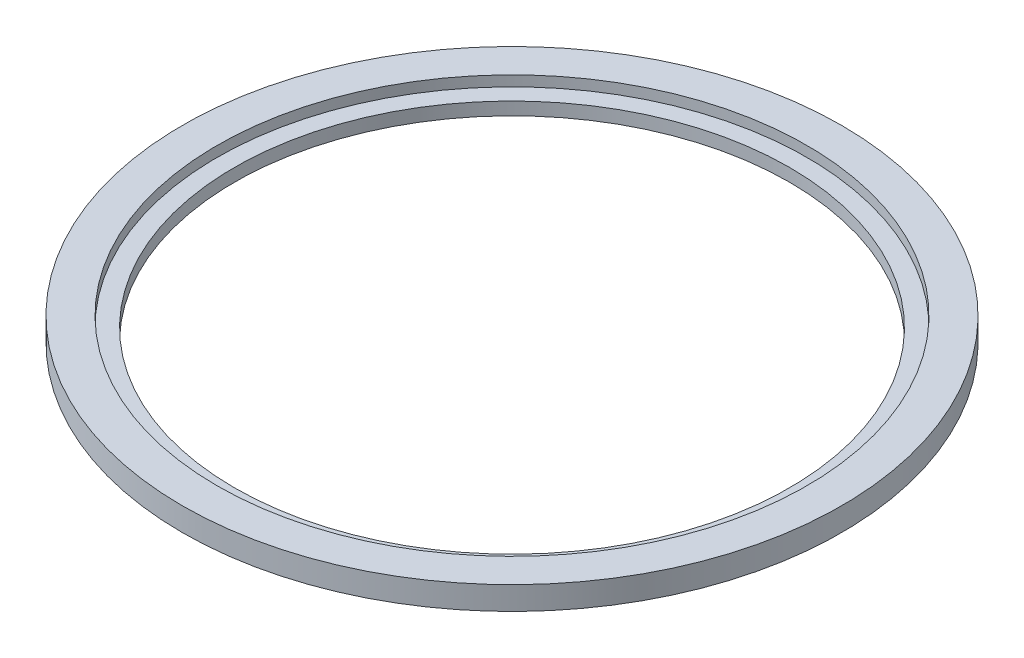
SolidWorks part; units mm, degrees
material "Balsa"
ref_plane "Front Plane" through (0, 0, 0) normal (0, 0, 1) x (1, 0, 0)
ref_plane "Top Plane" through (0, 0, 0) normal (0, 1, 0) x (1, 0, 0)
ref_plane "Right Plane" through (0, 0, 0) normal (1, 0, 0) x (0, 0, -1)
sketch "Sketch1" plane through (0, 0, 0) normal (0, 1, 0) x (1, 0, 0)
  circle A0 centre (0, 0) radius 95
  circle A1 centre (0, 0) radius 80
  dimension "D1" = 95
  dimension "D2" = 80
extrude "Boss-Extrude1" add sketch "Sketch1" along normal blind 6.7 contours A0
sketch "Sketch2" plane through (0, 6.7, 0) normal (0, 1, 0) x (1, 0, 0)
  circle A0 centre (0, 0) radius 85
  dimension "D1" = 85
extrude "Cut-Extrude1" cut sketch "Sketch2" against normal blind 3
equation "\"Ring inner radius\"= 80mm"
equation "\"D1@Sketch1\" = \"Bottom ring outer radius\""
equation "\"Heart cable hole radius\"= 3.5mm"
equation "\"Dogbone radius\"= 3mm"
equation "\"Tree side stock thickness\"= 6.7mm"
equation "\"Ring stock thickness\"= 6.7mm"
equation "\"D1@Boss-Extrude1\"= \"Ring stock thickness\""
equation "\"Tree teeth\"= 15mm"
equation "\"Tree slot\"= 15mm"
equation "\"Bottom ring outer radius\"= \"Ring inner radius\" + \"Tree teeth\""
equation "\"Cut-Extrude Tolerance\"= 5mm"
equation "\"Ring outer radius\"= \"Ring inner radius\" + \"Tree slot\" + 10"
equation "\"D2@Sketch1\"= \"Ring inner radius\""
equation "\"Plexiglass step\"= 5mm"
equation "\"Plexiglass thickness\"= 3mm"
equation "\"D1@Sketch2\"=\"Ring inner radius\" + \"Plexiglass step\""
